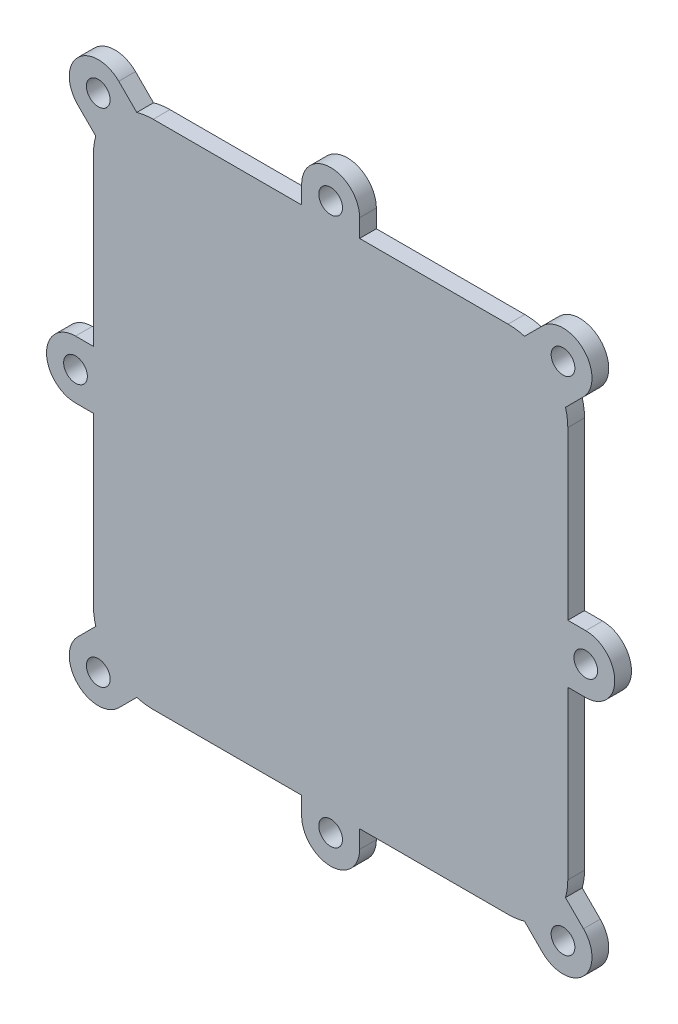
SolidWorks part; units mm, degrees
material "Acrylic (Medium-high impact)"
ref_plane "X-Y Datum" through (0, 0, 0) normal (0, 0, 1) x (1, 0, 0)
ref_plane "X-Z Datum" through (0, 0, 0) normal (0, 1, 0) x (1, 0, 0)
ref_plane "Y-Z Datum" through (0, 0, 0) normal (1, 0, 0) x (0, 0, -1)
sketch "Sketch1" plane through (0, 0, 0) normal (0, 0, 1) x (1, 0, 0)
  line L6 (37.3502, -76.716) -> (65.5162, -76.716)
  line L8 (65.5162, -76.716) -> (65.5162, -80.1257)
  line L9 (76.5162, -80.1257) -> (76.5162, -76.716)
  line L12 (76.5162, -76.716) -> (104.6822, -76.716)
  line L77 (37.3502, -76.716) -> (65.5162, -76.716)
  line L78 (37.3502, -76.716) -> (65.5162, -76.716)
  line L79 (65.5162, -76.716) -> (65.5162, -80.1257)
  line L96 (26.0162, 8.95) -> (26.0162, -22.716)
  line L97 (26.0162, -22.716) -> (22.6065, -22.716)
  line L105 (22.6065, -33.716) -> (26.0162, -33.716)
  line L106 (26.0162, -33.716) -> (26.0162, -65.382)
  line L109 (26.4536, -68.5004) -> (23.0357, -71.9183)
  line L110 (30.8139, -79.6965) -> (34.2318, -76.2786)
  line L117 (107.8006, -76.2786) -> (111.2185, -79.6965)
  line L118 (118.9966, -71.9183) -> (115.5788, -68.5004)
  line L120 (116.0162, -65.382) -> (116.0162, -33.716)
  line L124 (116.0162, -33.716) -> (119.4259, -33.716)
  line L125 (119.4259, -22.716) -> (116.0162, -22.716)
  line L126 (116.0162, -22.716) -> (116.0162, 8.95)
  line L128 (115.5788, 12.0683) -> (118.9966, 15.4862)
  line L130 (111.2185, 23.2644) -> (107.8006, 19.8465)
  line L131 (104.6822, 20.284) -> (76.5162, 20.284)
  line L155 (76.5162, 20.284) -> (76.5162, 23.6937)
  line L156 (65.5162, 23.6937) -> (65.5162, 20.284)
  line L157 (65.5162, 20.284) -> (37.3502, 20.284)
  line L158 (34.2318, 19.8465) -> (30.8139, 23.2644)
  line L159 (23.0357, 15.4862) -> (26.4536, 12.0683)
  line L160 (26.0162, 8.95) -> (26.0162, -22.716)
  line L161 (26.0162, -22.716) -> (22.6065, -22.716)
  line L162 (22.6065, -33.716) -> (26.0162, -33.716)
  line L163 (26.0162, -33.716) -> (26.0162, -65.382)
  line L164 (26.4536, -68.5004) -> (23.0357, -71.9183)
  line L165 (30.8139, -79.6965) -> (34.2318, -76.2786)
  line L170 (107.8006, -76.2786) -> (111.2185, -79.6965)
  line L171 (118.9966, -71.9183) -> (115.5788, -68.5004)
  line L172 (116.0162, -65.382) -> (116.0162, -33.716)
  line L173 (116.0162, -33.716) -> (119.4259, -33.716)
  line L174 (119.4259, -22.716) -> (116.0162, -22.716)
  line L175 (116.0162, -22.716) -> (116.0162, 8.95)
  line L176 (115.5788, 12.0683) -> (118.9966, 15.4862)
  line L177 (111.2185, 23.2644) -> (107.8006, 19.8465)
  line L178 (104.6822, 20.284) -> (76.5162, 20.284)
  line L179 (76.5162, 20.284) -> (76.5162, 23.6937)
  line L180 (65.5162, 23.6937) -> (65.5162, 20.284)
  line L181 (65.5162, 20.284) -> (37.3502, 20.284)
  line L182 (34.2318, 19.8465) -> (30.8139, 23.2644)
  line L183 (23.0357, 15.4862) -> (26.4536, 12.0683)
  line L220 (65.5162, -76.716) -> (65.5162, -80.1257)
  line L221 (76.5162, -80.1257) -> (76.5162, -76.716)
  line L222 (76.5162, -80.1257) -> (76.5162, -76.716)
  line L223 (76.5162, -76.716) -> (104.6822, -76.716)
  line L224 (76.5162, -76.716) -> (104.6822, -76.716)
  arc A66 (22.6065, -22.716) -> (22.6065, -33.716) centre (22.6065, -28.216) ccw
  arc A67 (26.0162, -65.382) -> (26.4536, -68.5004) centre (37.3502, -65.382) ccw
  arc A68 (23.0357, -71.9183) -> (30.8139, -79.6965) centre (26.9248, -75.8074) ccw
  arc A69 (34.2318, -76.2786) -> (37.3502, -76.716) centre (37.3502, -65.382) ccw
  arc A71 (104.6822, -76.716) -> (107.8006, -76.2786) centre (104.6822, -65.382) ccw
  arc A72 (111.2185, -79.6965) -> (118.9966, -71.9183) centre (115.1076, -75.8074) ccw
  arc A73 (115.5788, -68.5004) -> (116.0162, -65.382) centre (104.6822, -65.382) ccw
  arc A74 (119.4259, -33.716) -> (119.4259, -22.716) centre (119.4259, -28.216) ccw
  arc A75 (116.0162, 8.95) -> (115.5788, 12.0683) centre (104.6822, 8.95) ccw
  arc A76 (118.9966, 15.4862) -> (111.2185, 23.2644) centre (115.1076, 19.3753) ccw
  arc A107 (107.8006, 19.8465) -> (104.6822, 20.284) centre (104.6822, 8.95) ccw
  arc A108 (76.5162, 23.6937) -> (65.5162, 23.6937) centre (71.0162, 23.6937) ccw
  arc A109 (37.3502, 20.284) -> (34.2318, 19.8465) centre (37.3502, 8.95) ccw
  arc A110 (30.8139, 23.2644) -> (23.0357, 15.4862) centre (26.9248, 19.3753) ccw
  arc A111 (26.4536, 12.0683) -> (26.0162, 8.95) centre (37.3502, 8.95) ccw
  arc A112 (22.6065, -22.716) -> (22.6065, -33.716) centre (22.6065, -28.216) ccw
  arc A113 (26.0162, -65.382) -> (26.4536, -68.5004) centre (37.3502, -65.382) ccw
  arc A114 (23.0357, -71.9183) -> (30.8139, -79.6965) centre (26.9248, -75.8074) ccw
  arc A115 (34.2318, -76.2786) -> (37.3502, -76.716) centre (37.3502, -65.382) ccw
  arc A117 (104.6822, -76.716) -> (107.8006, -76.2786) centre (104.6822, -65.382) ccw
  arc A118 (111.2185, -79.6965) -> (118.9966, -71.9183) centre (115.1076, -75.8074) ccw
  arc A119 (115.5788, -68.5004) -> (116.0162, -65.382) centre (104.6822, -65.382) ccw
  arc A120 (119.4259, -33.716) -> (119.4259, -22.716) centre (119.4259, -28.216) ccw
  arc A121 (116.0162, 8.95) -> (115.5788, 12.0683) centre (104.6822, 8.95) ccw
  arc A122 (118.9966, 15.4862) -> (111.2185, 23.2644) centre (115.1076, 19.3753) ccw
  arc A123 (107.8006, 19.8465) -> (104.6822, 20.284) centre (104.6822, 8.95) ccw
  arc A124 (76.5162, 23.6937) -> (65.5162, 23.6937) centre (71.0162, 23.6937) ccw
  arc A125 (37.3502, 20.284) -> (34.2318, 19.8465) centre (37.3502, 8.95) ccw
  arc A126 (30.8139, 23.2644) -> (23.0357, 15.4862) centre (26.9248, 19.3753) ccw
  arc A127 (26.4536, 12.0683) -> (26.0162, 8.95) centre (37.3502, 8.95) ccw
  arc A143 (65.5162, -80.1257) -> (76.5162, -80.1257) centre (71.0162, -80.1257) ccw
  arc A144 (65.5162, -80.1257) -> (76.5162, -80.1257) centre (71.0162, -80.1257) ccw
  dimension "D1" = 0
extrude "Boss-Extrude1" add sketch "Sketch1" along normal blind 3.175
hole_wizard "M4 Clearance Hole1" positions "Sketch2" profile "Sketch3" hole size "M4" standard "ANSI Metric" end condition through all
sketch "Sketch2" plane through (0, 0, 3.175) normal (0, 0, 1) x (1, 0, 0)
  point P0 (26.9248, -75.8074)
  point P2 (22.6065, -28.216)
  point P4 (71.0162, -80.1257)
  point P6 (115.1076, -75.8074)
  point P8 (119.4259, -28.216)
  point P10 (115.1076, 19.3753)
  point P12 (71.0162, 23.6937)
  point P14 (26.9248, 19.3753)
sketch "Sketch3" plane through (26.9248, -75.8074, 3.175) normal (1, 0, 0) x (0, -1, 0)
  line L0 (0, 0) -> (0, 3.175)
  line L1 (0, 3.175) -> (2.25, 3.175)
  line L2 (2.25, 3.175) -> (2.25, 0)
  line L5 (2.25, 0) -> (0, 0)
  line L11 (0, -6.35) -> (0, 107.95) construction
  dimension "Thru Hole Dia." = 4.5
  dimension "Thru Hole Depth" = 3.175
